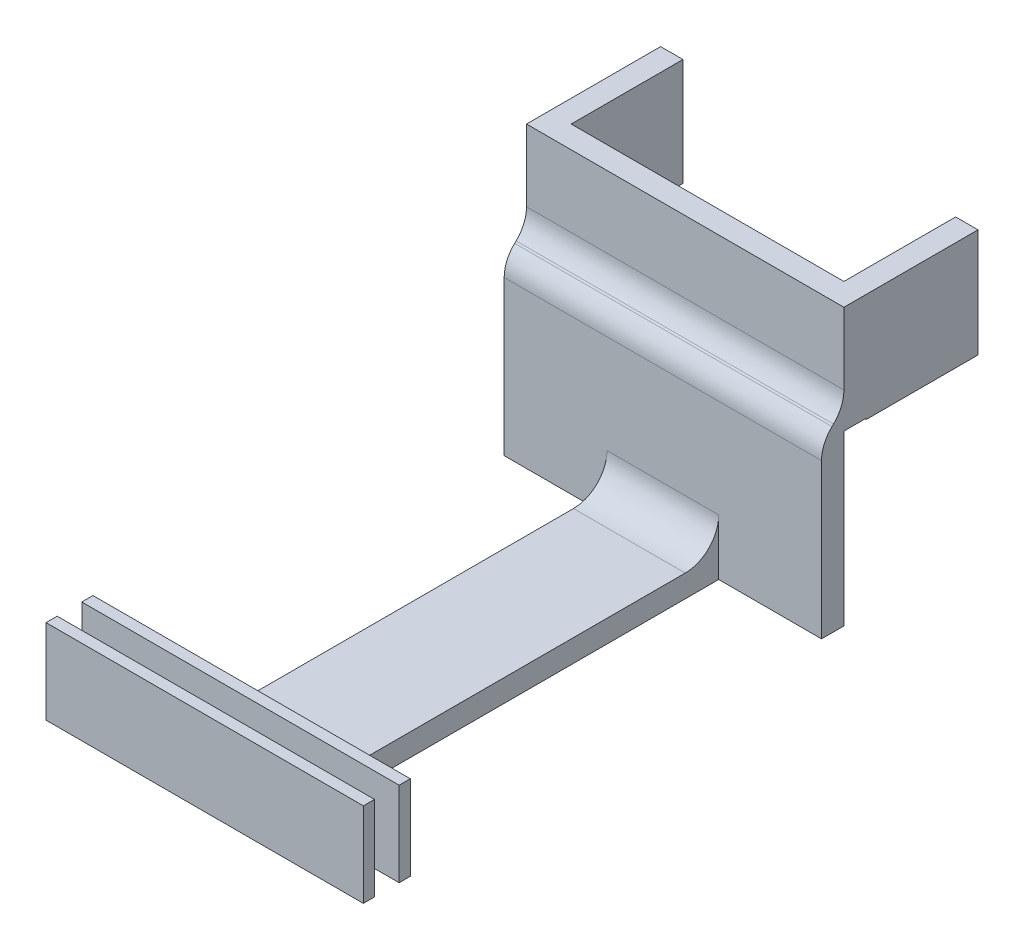
SolidWorks part; units mm, degrees
ref_plane "Plan de face" through (0, 0, 0) normal (0, 0, 1) x (1, 0, 0)
ref_plane "Plan de dessus" through (0, 0, 0) normal (0, 1, 0) x (1, 0, 0)
ref_plane "Plan de droite" through (0, 0, 0) normal (1, 0, 0) x (0, 0, -1)
sketch "Esquisse1" plane through (0, 0, 0) normal (0, 0, 1) x (1, 0, 0)
  line L1 (0, 0) -> (28.4, 0)
  line L2 (0, 0) -> (0, 15.1)
  line L3 (0, 15.1) -> (28.4, 15.1)
  line L4 (28.4, 0) -> (28.4, 15.1)
extrude "Boss.-Extru.1" add sketch "Esquisse1" along normal blind 2
sketch "Esquisse2" plane through (0, 0, 0) normal (0, 0, -1) x (-1, 0, 0)
  line L0 (-28.4, 0) -> (-28.4, 15.1) construction
  line L1 (-28.4, 15.1) -> (0, 15.1)
  line L2 (-28.4, 15.1) -> (-28.4, 24.7)
  line L3 (-28.4, 24.7) -> (0, 24.7)
  line L4 (0, 15.1) -> (0, 24.7)
  line L5 (-28.4, 15.1) -> (0, 15.1) construction
extrude "Boss.-Extru.2" add sketch "Esquisse2" along normal blind 2 separate body
sketch "Esquisse3" plane through (0, 0, -2) normal (0, 0, -1) x (-1, 0, 0)
  line L0 (-28.4, 15.1) -> (0, 15.1) construction
  line L1 (0, 15.1) -> (-2, 15.1)
  line L2 (0, 15.1) -> (0, 24.7)
  line L3 (0, 24.7) -> (-2, 24.7)
  line L4 (-2, 15.1) -> (-2, 24.7)
  line L5 (0, 24.7) -> (-28.4, 24.7) construction
  line L6 (-2, 24.7) -> (-26.4, 24.7) construction
  line L7 (-28.4, 15.1) -> (0, 15.1) construction
  line L8 (-26.4, 24.7) -> (-28.4, 24.7)
  line L9 (-26.4, 24.7) -> (-26.4, 15)
  line L10 (-26.4, 15) -> (-28.4, 15)
  line L11 (-28.4, 24.7) -> (-28.4, 15)
  point P14 (-14.2, 15.1)
  point P15 (-14.2, 24.7)
  dimension "D1" = 2
  dimension "D2" = 24.4
  dimension "D3" = 2
extrude "Boss.-Extru.3" add sketch "Esquisse3" along normal blind 10
sketch "Esquisse4" plane through (0, 0, 0) normal (0, -1, 0) x (1, 0, 0)
  line L0 (0, 2) -> (28.4, 2) construction
  line L1 (19.2, 2) -> (9.2, 2)
  line L2 (19.2, 2) -> (19.2, 42)
  line L3 (19.2, 42) -> (9.2, 42)
  line L4 (9.2, 2) -> (9.2, 42)
  line L5 (0, 0) -> (28.4, 0) construction
  point P8 (14.2, 0)
  point P9 (14.2, 2)
extrude "Boss.-Extru.4" add sketch "Esquisse4" against normal blind 2
sketch "Esquisse5" plane through (0, 0, 42) normal (0, 0, 1) x (1, 0, 0)
  line L0 (14.2, 0) -> (14.2, 2.5) construction
  line L1 (19.2, 0) -> (9.2, 0) construction
  line L2 (11.85, 0) -> (11.85, 2.5)
  line L3 (16.55, 0) -> (16.55, 2.5)
  line L4 (11.85, 2) -> (16.55, 2)
  line L5 (19.2, 2) -> (9.2, 2) construction
  arc A0 (11.85, 0) -> (16.55, 0) centre (14.2, 0) ccw construction
  arc A1 (16.55, 2.5) -> (11.85, 2.5) centre (14.2, 2.5) ccw
  point P4 (14.2, 1.25)
  point P9 (14.2, 4.85)
  line M6 (19.2, 2) -> (9.2, 2)
  dimension "D2" = 4.7
  dimension "D1" = 4.85
extrude "Boss.-Extru.5" add sketch "Esquisse5" against normal blind 2.2 contours L3 A1 L2 M6
sketch "Esquisse6" plane through (0, 0, 42) normal (0, 0, 1) x (1, 0, 0)
  line L0 (19.2, 0) -> (28.4, 0) construction
  line L1 (0, 7.5607) -> (28.4, 7.5607)
  line L2 (0, 7.5607) -> (0, 0)
  line L3 (0, 0) -> (28.4, 0)
  line L4 (28.4, 7.5607) -> (28.4, 0)
  line L7 (0, 15.1) -> (0, 0) construction
  arc A3 (16.55, 2.5) -> (11.85, 2.5) centre (14.2, 2.5) ccw construction
  point P9 (14.2, 4.85)
  point P10 (14.2, 0)
extrude "Boss.-Extru.6" add sketch "Esquisse6" along normal blind 1
pattern_linear "Répétition linéaire1" count 2 spacing 3.2 along (0, 0, -1) of "Boss.-Extru.6"
sketch "Esquisse7" plane through (0, 2, 0) normal (0, 1, 0) x (1, 0, 0)
  line L8 (19.2, -42) -> (19.2, -39.8) construction
  line L11 (19.2, -39.8) -> (16.55, -39.8) construction
  line L14 (16.55, -39.8) -> (16.55, -42) construction
  line L15 (16.55, -42) -> (19.2, -42) construction
  line L29 (11.85, -42) -> (11.85, -39.8) construction
  line L30 (11.85, -39.8) -> (9.2, -39.8) construction
  line L31 (9.2, -39.8) -> (9.2, -42) construction
  line L46 (9.2, -42) -> (11.85, -42) construction
  line L47 (19.2, -42) -> (19.2, -39.8)
  line L48 (19.2, -39.8) -> (16.55, -39.8)
  line L49 (16.55, -39.8) -> (16.55, -42)
  line L50 (16.55, -42) -> (19.2, -42)
  line L51 (11.85, -42) -> (11.85, -39.8)
  line L52 (11.85, -39.8) -> (9.2, -39.8)
  line L53 (9.2, -39.8) -> (9.2, -42)
  line L54 (9.2, -42) -> (11.85, -42)
extrude "Enlèv. mat.-Extru.1" cut sketch "Esquisse7" against normal through all
sketch "Esquisse9" plane through (0, 0, 0) normal (-1, 0, 0) x (0, 0, 1)
  line L0 (0, 15.1) -> (2, 15.1)
  line L1 (2, 15.1) -> (0, 17)
  line L2 (0, 15.1) -> (0, 24.7) construction
  line L3 (0, 17) -> (0, 15.1)
extrude "Boss.-Extru.7" add sketch "Esquisse9" against normal up to surface (28.4 mm away) up to face at (28.4, 18.2667, -4.6667)
fillet "Congé1" radius 3 4 edges at (14.2, 15.1, 2) (14.2, 17, 0) (14.2, 2, 2) (14.2, 2, 38.8)
